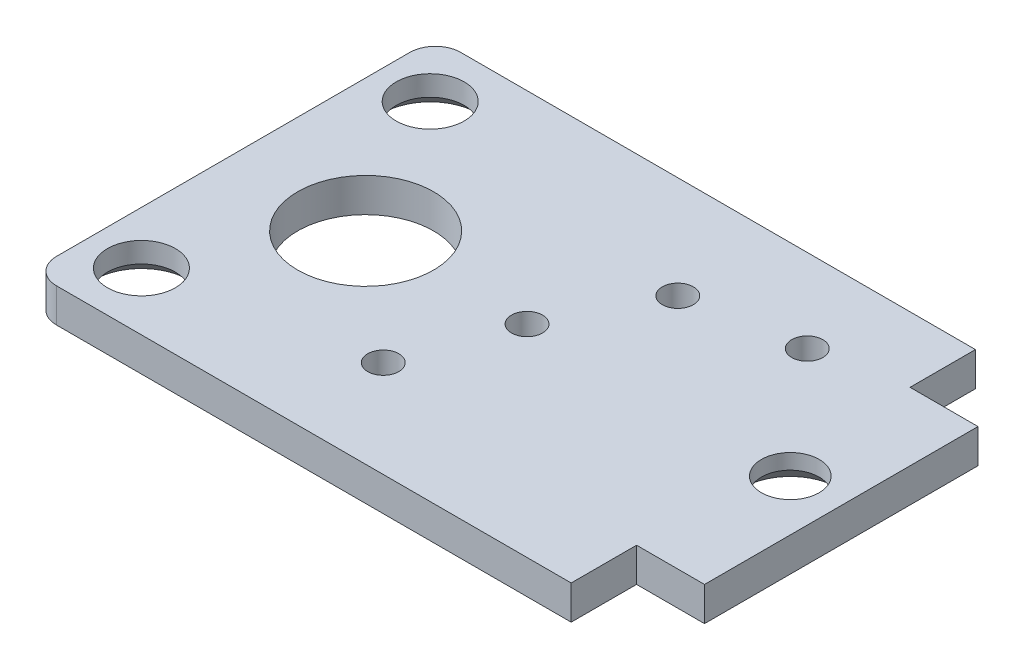
SolidWorks part; units mm, degrees
ref_plane "Front Plane" through (0, 0, 0) normal (0, 0, 1) x (1, 0, 0)
ref_plane "Top Plane" through (0, 0, 0) normal (0, 1, 0) x (1, 0, 0)
ref_plane "Right Plane" through (0, 0, 0) normal (1, 0, 0) x (0, 0, -1)
sketch "Sketch1" plane through (0, 0, 0) normal (0, 1, 0) x (1, 0, 0)
  line L1 (12, 5.95) -> (-3.9, 5.95)
  line L2 (14, 4.025) -> (14, -4.025)
  line L3 (12, -5.95) -> (-3.9, -5.95)
  line L4 (-3.9, 5.95) -> (-3.9, -5.95)
  line L5 (-0.55, 0) -> (0.55, 0) construction
  line L6 (12, 5.95) -> (12, 4.025)
  line L7 (0, -0.55) -> (0, 0.55) construction
  line L8 (12, 4.025) -> (14, 4.025)
  line L9 (12, -5.95) -> (12, -4.025)
  line L10 (12, -4.025) -> (14, -4.025)
  circle A0 centre (0, 0) radius 2
  point P0 (14, 0)
  point P2 (-3.9, 0)
  dimension "D4" = 4
  dimension "D6" = 2
  dimension "D1" = 14
  dimension "D2" = 17.9
  dimension "D3" = 11.9
  dimension "D5" = 8.05
extrude "Boss-Extrude1" add sketch "Sketch1" along normal blind 1
sketch "Sketch2" plane through (0, 1, 0) normal (0, 1, 0) x (1, 0, 0)
  line L0 (-2.35, 4.25) -> (-2.35, -4.25) construction
  line L1 (-0.55, 0) -> (0.55, 0) construction
  line L3 (14, -4.025) -> (14, 4.025) construction
  circle A0 centre (-2.35, 4.25) radius 1
  circle A1 centre (-2.35, -4.25) radius 1
  point P2 (-2.35, 0)
  dimension "D3" = 2
  dimension "D1" = 8.5
  dimension "D2" = 16.35
extrude "Cut-Extrude1" cut sketch "Sketch2" against normal through all
fillet "Fillet1" radius 0.75 2 edges at (-3.9, 0.5, -5.95) (-3.9, 0.5, 5.95)
chamfer "Chamfer1" distance 0.4 angle 45 2 edges at (-2.35, 0, 5.25) (-2.35, 0, -3.25)
sketch "Sketch3" plane through (0, 1, 0) normal (0, 1, 0) x (1, 0, 0)
  line L0 (-0.55, 0) -> (0.55, 0) construction
  line L1 (14, -4.025) -> (14, 4.025) construction
  circle A0 centre (3.6186, -3.1) radius 0.4572
  circle A1 centre (4.75, 0) radius 0.4572
  circle A2 centre (6.2478, 2.9405) radius 0.4572
  circle A3 centre (9.5, 3.5) radius 0.4572
  arc A5 (6.856, 1.5254) -> (6.3481, 4.4776) centre (9.5, 3.5) cw construction
  arc A6 (3.5785, 1.0001) -> (6.2478, -0.3595) centre (6.2478, 2.9405) ccw construction
  arc A7 (5.1489, -3.2758) -> (2.3349, -2.2488) centre (4.75, 0) cw construction
  point P19 (4.75, 0)
  point P22 (3.6186, -3.1)
  point P23 (6.2478, 2.9405)
  dimension "D1" = 0.9144
  dimension "D4" = 3.3
  dimension "D9" = 3.3
  dimension "D10" = 3.3
  dimension "D2" = 3.1
  dimension "D3" = 4.75
  dimension "D5" = 4.5
  dimension "D6" = 7.7522
  dimension "D7" = 10.3814
  dimension "D8" = 3.5
extrude "Cut-Extrude2" cut sketch "Sketch3" against normal through all
hole_wizard "CSK for M1.6 Countersunk Raised Head Screw2" positions "Sketch4" profile "Sketch5" countersink size "M1.6" standard "DIN" end condition through all
sketch "Sketch4" plane through (0, 0, 0) normal (0, 1, 0) x (1, 0, 0)
  line L0 (-0.55, 0) -> (0.55, 0) construction
  line L1 (14, -4.025) -> (14, 4.025) construction
  point P0 (12.5, 0)
  dimension "D1" = 1.5
sketch "Sketch5" plane through (12.5, 0, 0) normal (1, 0, 0) x (0, 0, -1)
  line L0 (0, 0) -> (0, 1)
  line L1 (0, 1) -> (0.85, 1)
  line L2 (0.85, 1) -> (0.85, 0.55)
  line L3 (0.85, 0.55) -> (1.4, 0)
  line L5 (1.4, 0) -> (0, 0)
  line L6 (-0.85, 0.55) -> (-1.4, 0) construction
  line L11 (0, -6.35) -> (0, 107.95) construction
  dimension "Thru Hole Dia." = 1.7
  dimension "Thru Hole Depth" = 1
  dimension "Near C'Sink Dia." = 2.8
  dimension "Near C'Sink Angle" = 90
